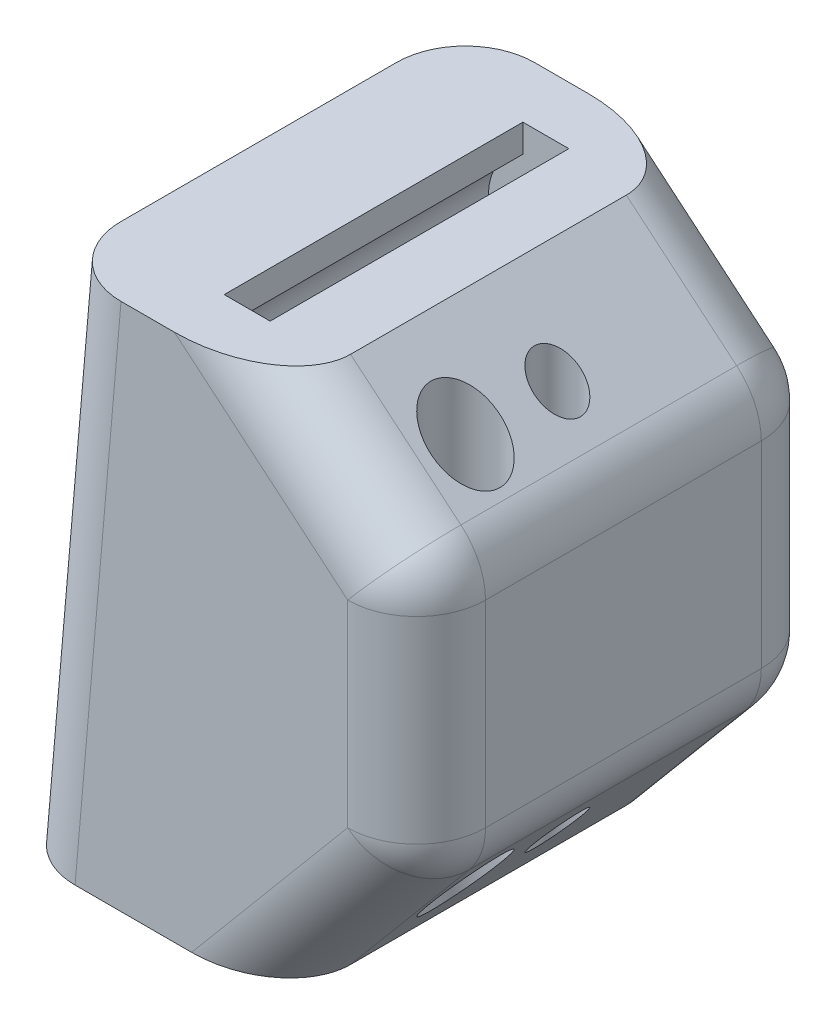
SolidWorks part; units mm, degrees
ref_plane "Front Plane" through (0, 0, 0) normal (0, 0, 1) x (1, 0, 0)
ref_plane "Top Plane" through (0, 0, 0) normal (0, 1, 0) x (1, 0, 0)
ref_plane "Right Plane" through (0, 0, 0) normal (1, 0, 0) x (0, 0, -1)
sketch "Sketch2" plane through (0, 0, 0) normal (0, 0, 1) x (1, 0, 0)
  line L0 (0, 0) -> (12, 0)
  line L1 (12, 0) -> (17.1718, 6.1635)
  line L2 (0, 0) -> (2, 23)
  line L3 (2, 23) -> (12, 23)
  line L4 (12, 23) -> (16.8021, 18.9706)
  line L5 (17.8737, 16.6725) -> (17.8737, 8.0919)
  arc A0 (16.8021, 18.9706) -> (17.8737, 16.6725) centre (14.8737, 16.6725) cw
  arc A1 (17.1718, 6.1635) -> (17.8737, 8.0919) centre (14.8737, 8.0919) ccw
  point P9 (17.8737, 18.0714)
  point P12 (17.8737, 7)
  dimension "D8" = 3
  dimension "D9" = 3
  dimension "D1" = 12
  dimension "D2" = 130
  dimension "D3" = 7
  dimension "D4" = 2
  dimension "D5" = 23
  dimension "D6" = 10
  dimension "D7" = 140
extrude "Boss-Extrude1" add sketch "Sketch2" along normal blind 18
sketch "Sketch3" plane through (0, 0, 18) normal (0, 0, 1) x (1, 0, 0)
  line L0 (12, 23) -> (2, 23) construction
  line L2 (7, 23) -> (9, 23)
  line L3 (7, 23) -> (7, 21.7913)
  line L5 (9, 23) -> (9, 21.7913)
  arc A0 (7, 21.7913) -> (9, 21.7913) centre (8, 19.5) ccw
  point P0 (8, 23)
  dimension "D2" = 5
  dimension "D1" = 8
  dimension "D3" = 3.5
  dimension "D4" = 2
  dimension "D5" = 1
extrude "Cut-Extrude1" cut sketch "Sketch3" against normal blind 13 from offset 2.5 offset against normal yes
sketch "Sketch4" plane through (0, 0, 0) normal (0, 0, -1) x (-1, 0, 0)
  line L0 (0, 0) -> (-12, 0) construction
  line L2 (-9, 0) -> (-7, 0)
  line L3 (-9, 0) -> (-9, 1.2087)
  line L5 (-7, 0) -> (-7, 1.2087)
  arc A0 (-7, 1.2087) -> (-9, 1.2087) centre (-8, 3.5) ccw
  point P0 (-8, 0)
  dimension "D2" = 5
  dimension "D1" = 8
  dimension "D3" = 3.5
  dimension "D4" = 2
  dimension "D5" = 1
extrude "Cut-Extrude2" cut sketch "Sketch4" against normal blind 13 from offset 2.5 offset against normal yes
sketch "Sketch5" plane through (0, 0, 0) normal (0, 1, 0) x (1, 0, 0)
  line L0 (12, -18) -> (12, 0) construction
  circle A0 centre (15, -9) radius 1
  circle A1 centre (15, -13) radius 1.5
  point P0 (12, -9)
  point P8 (0, 0)
  dimension "D1" = 2
  dimension "D4" = 3
  dimension "D2" = 3
  dimension "D3" = 15
  dimension "D5" = 4
extrude "Cut-Extrude3" cut sketch "Sketch5" along normal blind 25
fillet "Fillet1" radius 3 12 edges at (14.5859, 3.0818, 0) (17.6928, 7.0659, 0) (14.401, 20.9853, 0) (17.5926, 17.9403, 0) (14.5859, 3.0818, 18) (17.6928, 7.0659, 18) (14.401, 20.9853, 18) (17.5926, 17.9403, 18) (1, 11.5, 0) (17.8737, 12.3822, 0) (1, 11.5, 18) (17.8737, 12.3822, 18)
ref_plane "Plane1" through (0, 0, 9) normal (0, 0, 1) x (1, 0, 0)
